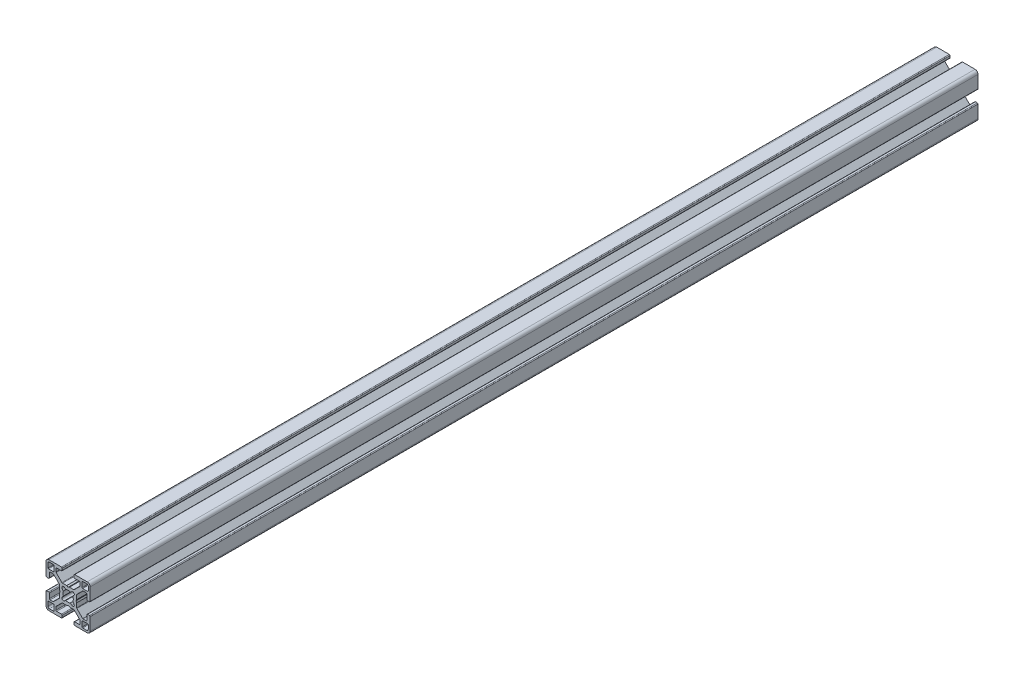
SolidWorks part; units mm, degrees
ref_plane "Plano frontal" through (0, 0, 0) normal (0, 0, 1) x (1, 0, 0)
ref_plane "Plano superior" through (0, 0, 0) normal (0, 1, 0) x (1, 0, 0)
ref_plane "Plano direito" through (0, 0, 0) normal (1, 0, 0) x (0, 0, -1)
ref_plane "Plano1"
sketch "Esboço1" plane through (0, 0, 0) normal (0, 0, 1) x (1, 0, 0)
  line L0 (-13, -15) -> (-4.508, -15)
  line L1 (-4, -14.492) -> (-4, -13.251)
  line L2 (-4.508, -12.743) -> (-7.742, -12.743)
  line L3 (-8.25, -12.235) -> (-8.25, -10.2642)
  line L4 (-8.1012, -9.905) -> (-4.1795, -5.9833)
  line L5 (-3.8203, -5.8345) -> (-0.949, -5.8345)
  line L6 (-0.949, -5.8345) -> (0, -5.325)
  line L7 (0, -5.325) -> (0.949, -5.8345)
  line L8 (0.949, -5.8345) -> (3.8216, -5.8345)
  line L9 (4.1808, -5.9833) -> (8.1012, -9.9037)
  line L10 (8.25, -10.2629) -> (8.25, -12.235)
  line L11 (7.742, -12.743) -> (4.508, -12.743)
  line L12 (4, -13.251) -> (4, -14.492)
  line L13 (4.508, -15) -> (13, -15)
  line L14 (15, -13) -> (15, -4.508)
  line L15 (14.492, -4) -> (13.251, -4)
  line L16 (12.743, -4.508) -> (12.743, -7.742)
  line L17 (12.235, -8.25) -> (10.2642, -8.25)
  line L18 (9.905, -8.1012) -> (5.9833, -4.1795)
  line L19 (5.8345, -3.8203) -> (5.8345, -0.949)
  line L20 (5.8345, -0.949) -> (5.325, 0)
  line L21 (5.325, 0) -> (5.8345, 0.949)
  line L22 (5.8345, 0.949) -> (5.8345, 3.8216)
  line L23 (5.9833, 4.1808) -> (9.9037, 8.1012)
  line L24 (10.2629, 8.25) -> (12.235, 8.25)
  line L25 (12.743, 7.742) -> (12.743, 4.508)
  line L26 (13.251, 4) -> (14.492, 4)
  line L27 (15, 4.508) -> (15, 13)
  line L28 (13, 15) -> (4.508, 15)
  line L29 (4, 14.492) -> (4, 13.251)
  line L30 (4.508, 12.743) -> (7.742, 12.743)
  line L31 (8.25, 12.235) -> (8.25, 10.2642)
  line L32 (8.1012, 9.905) -> (4.1795, 5.9833)
  line L33 (3.8203, 5.8345) -> (0.949, 5.8345)
  line L34 (0.949, 5.8345) -> (0, 5.325)
  line L35 (0, 5.325) -> (-0.949, 5.8345)
  line L36 (-0.949, 5.8345) -> (-3.8216, 5.8345)
  line L37 (-4.1808, 5.9833) -> (-8.1012, 9.9037)
  line L38 (-8.25, 10.2629) -> (-8.25, 12.235)
  line L39 (-7.742, 12.743) -> (-4.508, 12.743)
  line L40 (-4, 13.251) -> (-4, 14.492)
  line L41 (-4.508, 15) -> (-13, 15)
  line L42 (-15, 13) -> (-15, 4.508)
  line L43 (-14.492, 4) -> (-13.251, 4)
  line L44 (-12.743, 4.508) -> (-12.743, 7.742)
  line L45 (-12.235, 8.25) -> (-10.2642, 8.25)
  line L46 (-9.905, 8.1012) -> (-5.9833, 4.1795)
  line L47 (-5.8345, 3.8203) -> (-5.8345, 0.949)
  line L48 (-5.8345, 0.949) -> (-5.325, 0)
  line L49 (-5.325, 0) -> (-5.8345, -0.949)
  line L50 (-5.8345, -0.949) -> (-5.8345, -3.8216)
  line L51 (-5.9833, -4.1808) -> (-9.9037, -8.1012)
  line L52 (-10.2629, -8.25) -> (-12.235, -8.25)
  line L53 (-12.743, -7.742) -> (-12.743, -4.508)
  line L54 (-13.251, -4) -> (-14.492, -4)
  line L55 (-15, -4.508) -> (-15, -13)
  line L56 (9.5, 13.319) -> (9.5, 9.881)
  line L57 (9.881, 9.5) -> (13.319, 9.5)
  line L58 (13.7, 9.881) -> (13.7, 12.7)
  line L59 (12.7, 13.7) -> (9.881, 13.7)
  line L60 (9.5, -9.881) -> (9.5, -13.319)
  line L61 (9.881, -13.7) -> (12.7, -13.7)
  line L62 (13.7, -12.7) -> (13.7, -9.881)
  line L63 (13.319, -9.5) -> (9.881, -9.5)
  line L64 (-13.7, -9.881) -> (-13.7, -12.7)
  line L65 (-12.7, -13.7) -> (-9.881, -13.7)
  line L66 (-9.5, -13.319) -> (-9.5, -9.881)
  line L67 (-9.881, -9.5) -> (-13.319, -9.5)
  line L68 (-13.7, 12.7) -> (-13.7, 9.881)
  line L69 (-13.319, 9.5) -> (-9.881, 9.5)
  line L70 (-9.5, 9.881) -> (-9.5, 13.319)
  line L71 (-9.881, 13.7) -> (-12.7, 13.7)
  line L72 (-4.0107, 2.5139) -> (-3.1982, 1.4942)
  line L73 (-3.1982, -1.4942) -> (-4.0107, -2.5139)
  line L74 (-2.5139, -4.0107) -> (-1.4942, -3.1982)
  line L75 (1.4942, -3.1982) -> (2.5139, -4.0107)
  line L76 (4.0107, -2.5139) -> (3.1982, -1.4942)
  line L77 (3.1982, 1.4942) -> (4.0107, 2.5139)
  line L78 (2.5139, 4.0107) -> (1.4942, 3.1982)
  line L79 (-1.4942, 3.1982) -> (-2.5139, 4.0107)
  arc A0 (-15, -13) -> (-13, -15) centre (-13, -13) ccw
  arc A1 (-4.508, -15) -> (-4, -14.492) centre (-4.508, -14.492) ccw
  arc A2 (-4, -13.251) -> (-4.508, -12.743) centre (-4.508, -13.251) ccw
  arc A3 (-8.25, -12.235) -> (-7.742, -12.743) centre (-7.742, -12.235) ccw
  arc A4 (-8.1012, -9.905) -> (-8.25, -10.2642) centre (-7.742, -10.2642) ccw
  arc A5 (-3.8203, -5.8345) -> (-4.1795, -5.9833) centre (-3.8203, -6.3425) ccw
  arc A6 (4.1808, -5.9833) -> (3.8216, -5.8345) centre (3.8216, -6.3425) ccw
  arc A7 (8.25, -10.2629) -> (8.1012, -9.9037) centre (7.742, -10.2629) ccw
  arc A8 (7.742, -12.743) -> (8.25, -12.235) centre (7.742, -12.235) ccw
  arc A9 (4.508, -12.743) -> (4, -13.251) centre (4.508, -13.251) ccw
  arc A10 (4, -14.492) -> (4.508, -15) centre (4.508, -14.492) ccw
  arc A11 (13, -15) -> (15, -13) centre (13, -13) ccw
  arc A12 (15, -4.508) -> (14.492, -4) centre (14.492, -4.508) ccw
  arc A13 (13.251, -4) -> (12.743, -4.508) centre (13.251, -4.508) ccw
  arc A14 (12.235, -8.25) -> (12.743, -7.742) centre (12.235, -7.742) ccw
  arc A15 (9.905, -8.1012) -> (10.2642, -8.25) centre (10.2642, -7.742) ccw
  arc A16 (5.8345, -3.8203) -> (5.9833, -4.1795) centre (6.3425, -3.8203) ccw
  arc A17 (5.9833, 4.1808) -> (5.8345, 3.8216) centre (6.3425, 3.8216) ccw
  arc A18 (10.2629, 8.25) -> (9.9037, 8.1012) centre (10.2629, 7.742) ccw
  arc A19 (12.743, 7.742) -> (12.235, 8.25) centre (12.235, 7.742) ccw
  arc A20 (12.743, 4.508) -> (13.251, 4) centre (13.251, 4.508) ccw
  arc A21 (14.492, 4) -> (15, 4.508) centre (14.492, 4.508) ccw
  arc A22 (15, 13) -> (13, 15) centre (13, 13) ccw
  arc A23 (4.508, 15) -> (4, 14.492) centre (4.508, 14.492) ccw
  arc A24 (4, 13.251) -> (4.508, 12.743) centre (4.508, 13.251) ccw
  arc A25 (8.25, 12.235) -> (7.742, 12.743) centre (7.742, 12.235) ccw
  arc A26 (8.1012, 9.905) -> (8.25, 10.2642) centre (7.742, 10.2642) ccw
  arc A27 (3.8203, 5.8345) -> (4.1795, 5.9833) centre (3.8203, 6.3425) ccw
  arc A28 (-4.1808, 5.9833) -> (-3.8216, 5.8345) centre (-3.8216, 6.3425) ccw
  arc A29 (-8.25, 10.2629) -> (-8.1012, 9.9037) centre (-7.742, 10.2629) ccw
  arc A30 (-7.742, 12.743) -> (-8.25, 12.235) centre (-7.742, 12.235) ccw
  arc A31 (-4.508, 12.743) -> (-4, 13.251) centre (-4.508, 13.251) ccw
  arc A32 (-4, 14.492) -> (-4.508, 15) centre (-4.508, 14.492) ccw
  arc A33 (-13, 15) -> (-15, 13) centre (-13, 13) ccw
  arc A34 (-15, 4.508) -> (-14.492, 4) centre (-14.492, 4.508) ccw
  arc A35 (-13.251, 4) -> (-12.743, 4.508) centre (-13.251, 4.508) ccw
  arc A36 (-12.235, 8.25) -> (-12.743, 7.742) centre (-12.235, 7.742) ccw
  arc A37 (-9.905, 8.1012) -> (-10.2642, 8.25) centre (-10.2642, 7.742) ccw
  arc A38 (-5.8345, 3.8203) -> (-5.9833, 4.1795) centre (-6.3425, 3.8203) ccw
  arc A39 (-5.9833, -4.1808) -> (-5.8345, -3.8216) centre (-6.3425, -3.8216) ccw
  arc A40 (-10.2629, -8.25) -> (-9.9037, -8.1012) centre (-10.2629, -7.742) ccw
  arc A41 (-12.743, -7.742) -> (-12.235, -8.25) centre (-12.235, -7.742) ccw
  arc A42 (-12.743, -4.508) -> (-13.251, -4) centre (-13.251, -4.508) ccw
  arc A43 (-14.492, -4) -> (-15, -4.508) centre (-14.492, -4.508) ccw
  arc A44 (9.5, 9.881) -> (9.881, 9.5) centre (9.881, 9.881) ccw
  arc A45 (13.319, 9.5) -> (13.7, 9.881) centre (13.319, 9.881) ccw
  arc A46 (13.7, 12.7) -> (12.7, 13.7) centre (12.7, 12.7) ccw
  arc A47 (9.881, 13.7) -> (9.5, 13.319) centre (9.881, 13.319) ccw
  arc A48 (9.5, -13.319) -> (9.881, -13.7) centre (9.881, -13.319) ccw
  arc A49 (12.7, -13.7) -> (13.7, -12.7) centre (12.7, -12.7) ccw
  arc A50 (13.7, -9.881) -> (13.319, -9.5) centre (13.319, -9.881) ccw
  arc A51 (9.881, -9.5) -> (9.5, -9.881) centre (9.881, -9.881) ccw
  arc A52 (-13.7, -12.7) -> (-12.7, -13.7) centre (-12.7, -12.7) ccw
  arc A53 (-9.881, -13.7) -> (-9.5, -13.319) centre (-9.881, -13.319) ccw
  arc A54 (-9.5, -9.881) -> (-9.881, -9.5) centre (-9.881, -9.881) ccw
  arc A55 (-13.319, -9.5) -> (-13.7, -9.881) centre (-13.319, -9.881) ccw
  arc A56 (-13.7, 9.881) -> (-13.319, 9.5) centre (-13.319, 9.881) ccw
  arc A57 (-9.881, 9.5) -> (-9.5, 9.881) centre (-9.881, 9.881) ccw
  arc A58 (-9.5, 13.319) -> (-9.881, 13.7) centre (-9.881, 13.319) ccw
  arc A59 (-12.7, 13.7) -> (-13.7, 12.7) centre (-12.7, 12.7) ccw
  arc A60 (-2.5139, 4.0107) -> (-4.0107, 2.5139) centre (-3.142, 3.142) ccw
  arc A61 (-3.1982, 1.4942) -> (-3.1982, -1.4942) centre (0, 0) ccw
  arc A62 (-4.0107, -2.5139) -> (-2.5139, -4.0107) centre (-3.142, -3.142) ccw
  arc A63 (-1.4942, -3.1982) -> (1.4942, -3.1982) centre (0, 0) ccw
  arc A64 (2.5139, -4.0107) -> (4.0107, -2.5139) centre (3.142, -3.142) ccw
  arc A65 (3.1982, -1.4942) -> (3.1982, 1.4942) centre (0, 0) ccw
  arc A66 (4.0107, 2.5139) -> (2.5139, 4.0107) centre (3.142, 3.142) ccw
  arc A67 (1.4942, 3.1982) -> (-1.4942, 3.1982) centre (0, 0) ccw
extrude "Extrusion1" add sketch "Esboço1" against normal blind 603 contours L54 A43 L55 A0 L0 A1 L1 A2 L2 A3 L3 A4 L4 A5 L5 L6 L7 L8 A6 L9 A7 L10 A8 L11 A9 L12 A10 L13 A11 L14 A12 L15 A13 L16 A14 L17 A15 L18 A16 L19 L20 L21 L22 A17 L23 A18 L24 A19 L25 A20 L26
